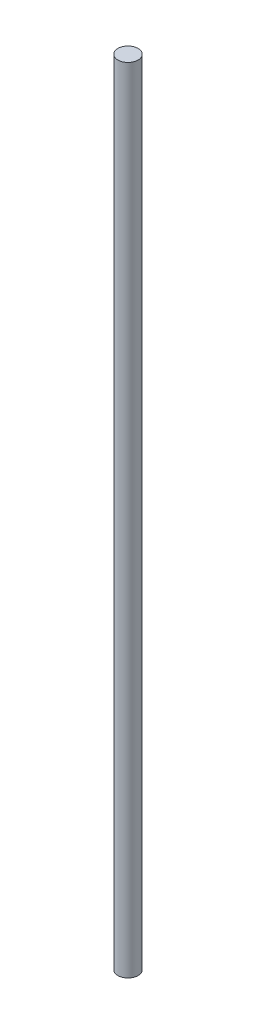
SolidWorks part; units mm, degrees
ref_plane "Front" through (0, 0, 0) normal (0, 0, 1) x (1, 0, 0)
ref_plane "Top" through (0, 0, 0) normal (0, 1, 0) x (1, 0, 0)
ref_plane "Right" through (0, 0, 0) normal (1, 0, 0) x (0, 0, -1)
sketch "Sketch1" plane through (0, 0, 0) normal (0, 1, 0) x (1, 0, 0)
  circle A0 centre (0, 0) radius 1.525
  dimension "D1" = 3.05
extrude "Boss-Extrude1" add sketch "Sketch1" along normal blind 120
